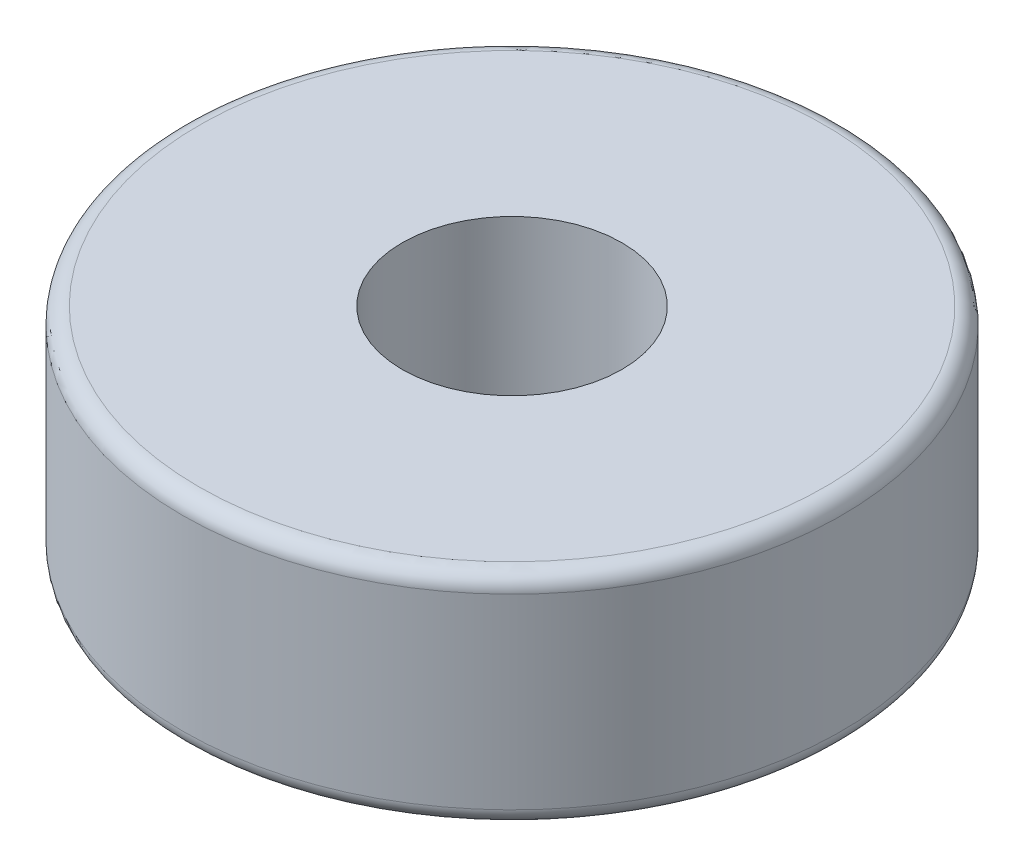
SolidWorks part; units mm, degrees
material "合金钢"
ref_plane "前视基准面" through (0, 0, 0) normal (0, 0, 1) x (1, 0, 0)
ref_plane "上视基准面" through (0, 0, 0) normal (0, 1, 0) x (1, 0, 0)
ref_plane "右视基准面" through (0, 0, 0) normal (1, 0, 0) x (0, 0, -1)
sketch "草图1" plane through (0, 0, 0) normal (0, 1, 0) x (1, 0, 0)
  circle A0 centre (0, 0) radius 6
  circle A1 centre (0, 0) radius 2
  dimension "D1" = 12
  dimension "D2" = 4
extrude "凸台-拉伸1" add sketch "草图1" along normal blind 4
fillet "圆角1" radius 0.3 2 edges at (0, 0, 6) (0, 4, 6)
